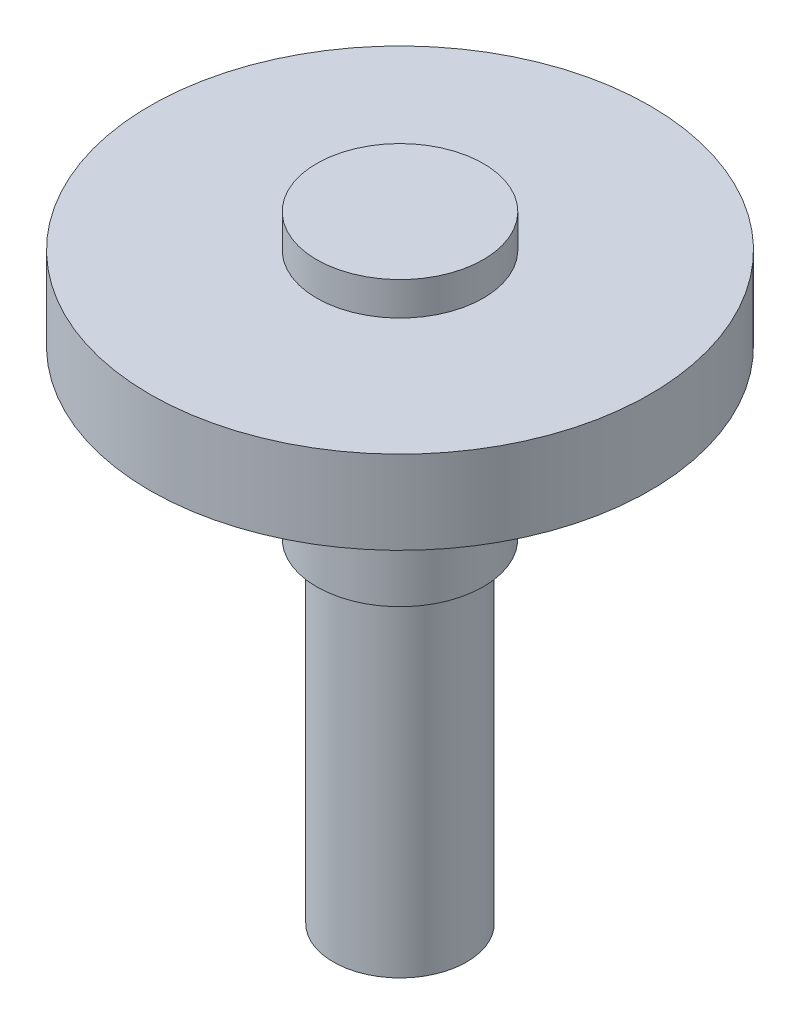
SolidWorks part; units mm, degrees
material "6061 Alloy"
ref_plane "Plano frontal" through (0, 0, 0) normal (0, 0, 1) x (1, 0, 0)
ref_plane "Plano superior" through (0, 0, 0) normal (0, 1, 0) x (1, 0, 0)
ref_plane "Plano direito" through (0, 0, 0) normal (1, 0, 0) x (0, 0, -1)
sketch "Sketch1" plane through (0, 0, 0) normal (0, 1, 0) x (1, 0, 0)
  circle A0 centre (0, 0) radius 15
  dimension "D1" = 30
extrude "Boss-Extrude1" add sketch "Sketch1" along normal blind 5
sketch "Sketch3" plane through (0, 5, 0) normal (0, 1, 0) x (1, 0, 0)
  circle A1 centre (0, 0) radius 5
  dimension "D1" = 10
extrude "Boss-Extrude2" add sketch "Sketch3" along normal blind 2
sketch "Sketch2" plane through (0, 0, 0) normal (0, -1, 0) x (1, 0, 0)
  circle A0 centre (0, 0) radius 5
  dimension "D1" = 10
extrude "Boss-Extrude3" add sketch "Sketch2" along normal blind 10
sketch "Sketch4" plane through (0, -10, 0) normal (0, -1, 0) x (1, 0, 0)
  circle A0 centre (0, 0) radius 4
  dimension "D1" = 8
extrude "Boss-Extrude4" add sketch "Sketch4" along normal blind 20
